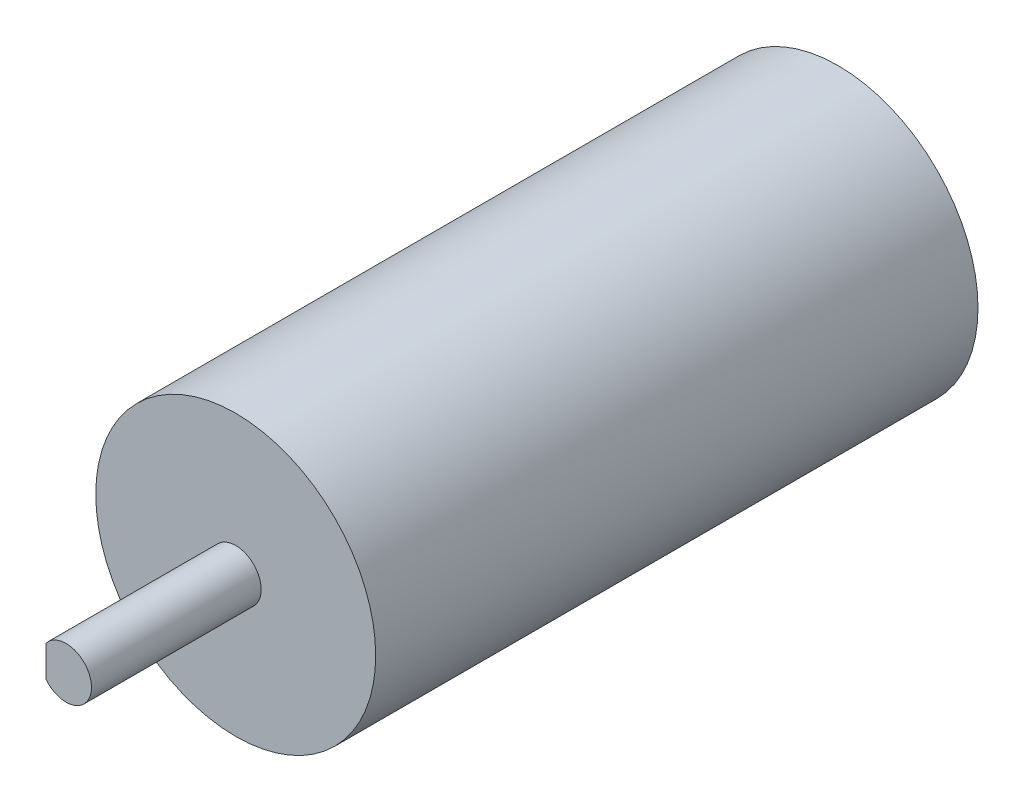
SolidWorks part; units mm, degrees
ref_plane "Plan de face" through (0, 0, 0) normal (0, 0, 1) x (1, 0, 0)
ref_plane "Plan de dessus" through (0, 0, 0) normal (0, 1, 0) x (1, 0, 0)
ref_plane "Plan de droite" through (0, 0, 0) normal (1, 0, 0) x (0, 0, -1)
sketch "Esquisse1" plane through (0, 0, 0) normal (0, 0, 1) x (1, 0, 0)
  circle A0 centre (-3.9364, 11.8284) radius 16.5
extrude "Boss.-Extru.1" add sketch "Esquisse1" along normal blind 71
sketch "Esquisse2" plane through (0, 0, 71) normal (0, 0, 1) x (1, 0, 0)
  circle A0 centre (-3.9364, 11.8284) radius 3
  circle A1 centre (-3.9364, 11.8284) radius 16.5 construction
  dimension "D1" = 0
extrude "Boss.-Extru.2" add sketch "Esquisse2" along normal blind 20
sketch "Esquisse3" plane through (0, 0, 71) normal (0, 0, 1) x (1, 0, 0)
  line L1 (-8.9857, 15.3679) -> (-6.3018, 15.3679)
  line L2 (-8.9857, 15.3679) -> (-8.9857, 7.3022)
  line L3 (-8.9857, 7.3022) -> (-6.3018, 7.3022)
  line L4 (-6.3018, 15.3679) -> (-6.3018, 7.3022)
extrude "Enlèv. mat.-Extru.1" cut sketch "Esquisse3" along normal blind 23
